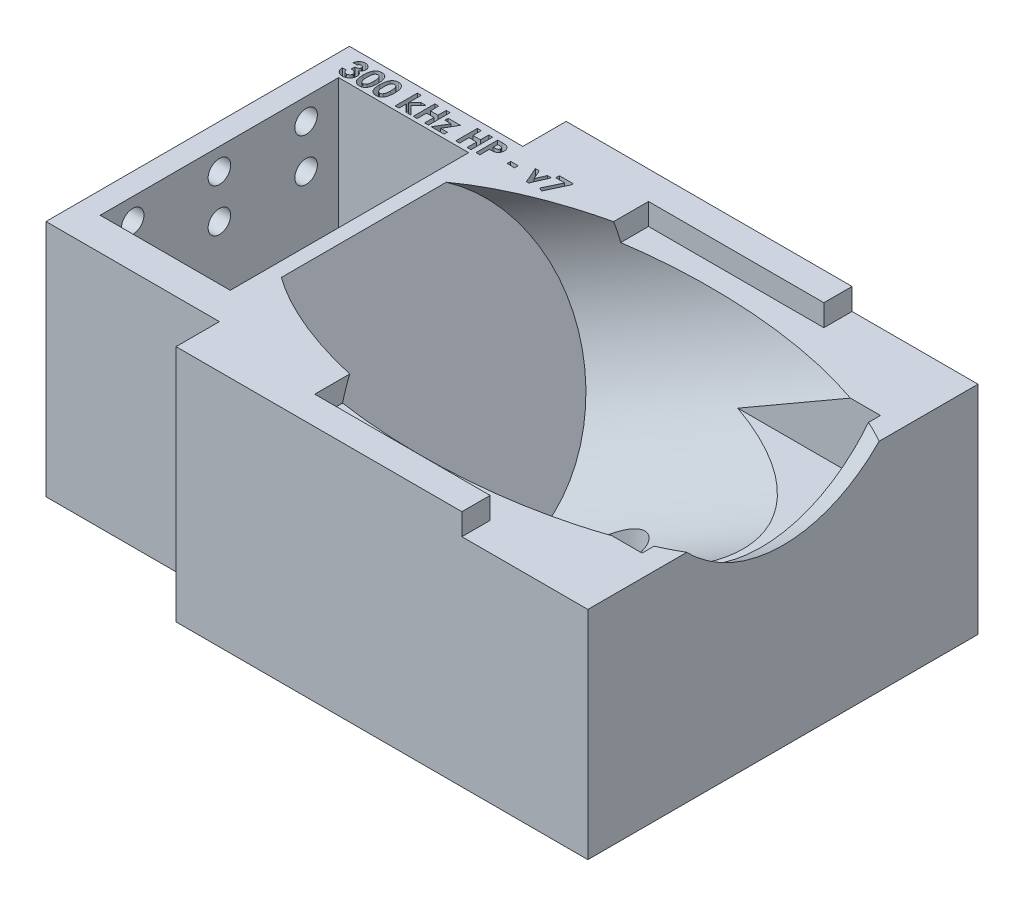
SolidWorks part; units mm, degrees
ref_plane "Front Plane" through (0, 0, 0) normal (0, 0, 1) x (1, 0, 0)
ref_plane "Top Plane" through (0, 0, 0) normal (0, 1, 0) x (1, 0, 0)
ref_plane "Right Plane" through (0, 0, 0) normal (1, 0, 0) x (0, 0, -1)
sketch "Sketch1" plane through (0, 0, 0) normal (0, 0, 1) x (1, 0, 0)
  line L1 (-139.7, -127) -> (88.9, -127)
  line L2 (-139.7, -127) -> (-139.7, 0)
  line L3 (-139.7, 0) -> (88.9, 0)
  line L4 (88.9, -127) -> (88.9, 0)
  line L5 (-139.7, -127) -> (88.9, 0) construction
  line L6 (-139.7, 0) -> (88.9, -127) construction
  point P0 (0, 0)
  dimension "D1" = 228.6
  dimension "D2" = 127
  dimension "D3" = 88.9
extrude "Boss-Extrude1" add sketch "Sketch1" along normal mid plane 101.6
sketch "Sketch10" plane through (0, -127, 0) normal (0, -1, 0) x (1, 0, 0)
  circle A0 centre (0, 0) radius 12.7
  dimension "D1" = 25.4
extrude "Cut-Extrude6" cut sketch "Sketch10" against normal through all
sketch "Sketch2" plane through (0, 0, 0) normal (0, 0, 1) x (1, 0, 0)
  line L0 (-48.125, -30.325) -> (0, -2.54) construction
  line L1 (0, 46.5867) -> (-47.9201, 18.9201)
  line L2 (-50.1425, -26.8306) -> (-69.3975, 6.5201)
  line L3 (-69.3975, 6.5201) -> (-47.9201, 18.9201)
  line L4 (-50.1425, -26.8306) -> (-48.125, -30.325)
  line L5 (-26.6476, -17.925) -> (-47.9201, 18.9201) construction
  line L7 (0, -2.54) -> (87.9882, 48.26)
  line L8 (-83.8, -2.54) -> (0, -2.54) construction
  line L10 (0, -2.54) -> (-48.125, -30.325)
  line L11 (88.9, 0) -> (-139.7, 0) construction
  line L12 (87.9882, 48.26) -> (66.7157, 85.1051)
  line L13 (0, 46.5867) -> (0, -2.54) construction
  line L17 (66.7157, 85.1051) -> (0, 46.5867)
  point P23 (-26.6476, -17.925)
  dimension "D1" = 30
  dimension "D2" = 24.8
  dimension "D3" = 2.54
  dimension "D4" = 30.77
  dimension "D5" = 42.545
  dimension "D6" = 101.6
revolve "Cut-Revolve1" cut sketch "Sketch2" angle 360 about L0
sketch "Sketch11" plane through (0, -127, 0) normal (0, -1, 0) x (1, 0, 0)
  line L1 (13, 13) -> (-13, 13)
  line L2 (13, 13) -> (13, -13)
  line L3 (13, -13) -> (-13, -13)
  line L4 (-13, 13) -> (-13, -13)
  line L5 (13, 13) -> (-13, -13) construction
  line L6 (13, -13) -> (-13, 13) construction
  point P0 (0, 0)
  dimension "D1" = 26
sketch "Sketch22" plane through (0, 0, 0) normal (0, 1, 0) x (1, 0, 0)
  line L0 (88.9, -50.8) -> (-139.7, -50.8) construction
  line L1 (-139.7, 50.8) -> (-114.3, 50.8)
  line L2 (-139.7, 50.8) -> (-139.7, -50.8)
  line L3 (-139.7, -50.8) -> (-114.3, -50.8)
  line L4 (-114.3, 50.8) -> (-114.3, -50.8)
  dimension "D1" = 25.4
extrude "Cut-Extrude17" cut sketch "Sketch22" against normal through all
sketch "Sketch23" plane through (0, -127, 0) normal (0, -1, 0) x (1, 0, 0)
  line L0 (-127, 127) -> (127, -127) construction
  line L1 (-127, 127) -> (127, 127)
  line L2 (-127, 127) -> (-127, -127)
  line L3 (-127, -127) -> (127, -127)
  line L4 (127, 127) -> (127, -127)
  dimension "D1" = 254
  dimension "D2" = 254
extrude "Cut-Extrude18" cut sketch "Sketch23" against normal blind 57.15
sketch "Sketch21" plane through (0, 0, 0) normal (0, 1, 0) x (1, 0, 0)
  line L1 (88.9, -50.8) -> (57.15, -50.8)
  line L2 (88.9, -50.8) -> (88.9, 50.8)
  line L3 (88.9, 50.8) -> (57.15, 50.8)
  line L4 (57.15, -50.8) -> (57.15, 50.8)
  line L5 (88.9, -50.8) -> (-114.3, -50.8) construction
  line L6 (88.9, 50.8) -> (-114.3, 50.8) construction
  line L7 (-114.3, -50.8) -> (-114.3, 50.8) construction
  dimension "D1" = 171.45
extrude "Cut-Extrude16" cut sketch "Sketch21" against normal through all
sketch "Sketch26" plane through (0, 0, 0) normal (0, 1, 0) x (1, 0, 0)
  line L0 (57.15, 50.8) -> (57.15, 33.3829) construction
  line L1 (-12.7, -34.925) -> (50.8, -34.925)
  line L2 (-12.7, -34.925) -> (-12.7, 34.925)
  line L3 (-12.7, 34.925) -> (50.8, 34.925)
  line L4 (50.8, -34.925) -> (50.8, 34.925)
  line L5 (-114.3, -50.8) -> (-114.3, 50.8) construction
  point P4 (-12.7, 0)
  dimension "D1" = 6.35
  dimension "D2" = 101.6
  dimension "D3" = 69.85
extrude "Cut-Extrude21" cut sketch "Sketch26" against normal blind 25.4
sketch "Sketch27" plane through (-114.3, 0, 0) normal (-1, 0, 0) x (0, 0, 1)
  line L0 (50.8, 0) -> (-50.8, 0) construction
  line L1 (-25.4, -6.35) -> (25.4, -6.35) construction
  line L2 (-25.4, -6.35) -> (-25.4, -19.05) construction
  line L3 (-25.4, -19.05) -> (25.4, -19.05) construction
  line L4 (25.4, -6.35) -> (25.4, -19.05) construction
  line L7 (-25.4, -19.05) -> (-25.4, -31.75) construction
  line L8 (-25.4, -31.75) -> (25.4, -31.75) construction
  line L9 (25.4, -19.05) -> (25.4, -31.75) construction
  circle A0 centre (-25.4, -6.35) radius 3.302
  circle A1 centre (0, -6.35) radius 3.302
  circle A2 centre (0, -19.05) radius 3.302
  circle A3 centre (25.4, -6.35) radius 3.302
  circle A4 centre (25.4, -19.05) radius 3.302
  circle A5 centre (-25.4, -19.05) radius 3.302
  circle A7 centre (-25.4, -31.75) radius 3.302 [skipped]
  circle A8 centre (0, -31.75) radius 3.302 [skipped]
  circle A9 centre (25.4, -31.75) radius 3.302 [skipped]
  point P4 (0, -6.35)
  dimension "D5" = 6.604
  dimension "D8" = 25.4
  dimension "D1" = 50.8
  dimension "D2" = 12.7
  dimension "D3" = 6.35
  dimension "D4" = 12.7
  dimension "D6" = 3
  dimension "D7" = 3
extrude "Cut-Extrude22" cut sketch "Sketch27" against normal blind 25.4 and the other way through all
sketch "Sketch28" plane through (0, 0, 0) normal (0, 1, 0) x (1, 0, 0)
  line L0 (-114.3, 36.0198) -> (-43.5568, 36.0198) construction
  line L3 (-114.3, -50.8) -> (-114.3, 50.8) construction
  text T0 "<b>300 kHz HP - v7</b>" font "Century Gothic" height 6.35
extrude "Cut-Extrude23" cut sketch "Sketch28" against normal blind 3.175
sketch "Sketch30" plane through (0, -25.4, 0) normal (0, 1, 0) x (1, 0, 0)
  circle A0 centre (-95.25, 25.4) radius 3.429
  circle A2 centre (-82.55, 25.4) radius 3.429
  circle A3 centre (-82.55, 12.7) radius 3.429
  circle A4 centre (-82.55, 0) radius 3.429
  circle A5 centre (-82.55, -12.7) radius 3.429
  circle A6 centre (-82.55, -25.4) radius 3.429
  circle A7 centre (-95.25, 12.7) radius 3.429
  circle A8 centre (-95.25, 0) radius 3.429
  circle A9 centre (-95.25, -12.7) radius 3.429
  circle A10 centre (-95.25, -25.4) radius 3.429
  dimension "D1" = 6.858
  dimension "D2" = 25.4
  dimension "D3" = 95.25
  dimension "D4" = 2
  dimension "D5" = 5
extrude "Cut-Extrude24" cut sketch "Sketch30" against normal through all
sketch "Sketch31" plane through (0, -25.4, 0) normal (0, 1, 0) x (1, 0, 0)
  line L0 (-107.95, -34.925) -> (-44.1937, -34.925) construction
  line L1 (-107.95, 34.925) -> (-69.85, 34.925)
  line L2 (-107.95, 34.925) -> (-107.95, -34.925)
  line L3 (-107.95, -34.925) -> (-69.85, -34.925)
  line L4 (-69.85, 34.925) -> (-69.85, -34.925)
  dimension "D1" = 38.1
extrude "Cut-Extrude25" cut sketch "Sketch31" against normal offset from surface 6.35 and the other way through all up to face at (-82.55, -69.85, 28.829)
sketch "Sketch32" plane through (0, 0, 0) normal (0, 1, 0) x (1, 0, 0)
  line L0 (57.15, 50.8) -> (57.15, 33.3829) construction
  line L1 (-31.1262, 48.895) -> (57.15, 48.895)
  line L2 (-31.1262, 48.895) -> (-31.1262, -48.895)
  line L3 (-31.1262, -48.895) -> (57.15, -48.895)
  line L4 (57.15, 48.895) -> (57.15, -48.895)
  point P4 (57.15, 0)
  dimension "D1" = 97.79
extrude "Cut-Extrude26" cut sketch "Sketch32" against normal blind 6.35
sketch "Sketch33" plane through (0, 0, 0) normal (0, 1, 0) x (1, 0, 0)
  line L1 (57.15, 50.8) -> (20.2503, 50.8)
  line L2 (57.15, 50.8) -> (57.15, -50.8)
  line L3 (57.15, -50.8) -> (20.2503, -50.8)
  line L4 (20.2503, 50.8) -> (20.2503, -50.8)
  line L5 (57.15, -50.8) -> (-114.3, -50.8) construction
extrude "Cut-Extrude27" cut sketch "Sketch33" against normal blind 6.35
sketch "Sketch34" plane through (0, 0, 50.8) normal (0, 0, 1) x (1, 0, 0)
  line L6 (57.15, -6.35) -> (20.2503, -6.35)
  line L7 (20.2503, -6.35) -> (20.2503, 0)
  line L8 (20.2503, 0) -> (-114.3, 0)
  line L9 (-114.3, 0) -> (-114.3, -69.85)
  line L10 (-114.3, -69.85) -> (57.15, -69.85)
  line L11 (57.15, -69.85) -> (57.15, -6.35)
  line L12 (57.15, -6.35) -> (20.2503, -6.35)
  line L13 (20.2503, -6.35) -> (20.2503, 0)
  line L14 (20.2503, 0) -> (-114.3, 0)
  line L15 (-114.3, 0) -> (-114.3, -69.85)
  line L16 (-114.3, -69.85) -> (57.15, -69.85)
  line L17 (57.15, -69.85) -> (57.15, -6.35)
  dimension "D1" = 0
extrude "Boss-Extrude2" add sketch "Sketch34" along normal blind 6.35
sketch "Sketch35" plane through (0, 0, -50.8) normal (0, 0, -1) x (-1, 0, 0)
  line L6 (-20.2503, 0) -> (-20.2503, -6.35)
  line L7 (-20.2503, -6.35) -> (-57.15, -6.35)
  line L8 (-57.15, -6.35) -> (-57.15, -69.85)
  line L9 (-57.15, -69.85) -> (114.3, -69.85)
  line L10 (114.3, -69.85) -> (114.3, 0)
  line L11 (114.3, 0) -> (-20.2503, 0)
  line L12 (-20.2503, 0) -> (-20.2503, -6.35)
  line L13 (-20.2503, -6.35) -> (-57.15, -6.35)
  line L14 (-57.15, -6.35) -> (-57.15, -69.85)
  line L15 (-57.15, -69.85) -> (114.3, -69.85)
  line L16 (114.3, -69.85) -> (114.3, 0)
  line L17 (114.3, 0) -> (-20.2503, 0)
  dimension "D1" = 0
extrude "Boss-Extrude3" add sketch "Sketch35" along normal blind 6.35
sketch "Sketch36" plane through (0, 0, 0) normal (0, 1, 0) x (1, 0, 0)
  line L0 (-114.3, -57.15) -> (-114.3, 57.15) construction
  line L1 (-114.3, 57.15) -> (-63.5, 57.15)
  line L2 (-114.3, 57.15) -> (-114.3, 44.45)
  line L3 (-114.3, 44.45) -> (-63.5, 44.45)
  line L4 (-63.5, 57.15) -> (-63.5, 44.45)
  line L5 (-114.3, -57.15) -> (-63.5, -57.15)
  line L6 (-114.3, -57.15) -> (-114.3, -44.45)
  line L7 (-114.3, -44.45) -> (-63.5, -44.45)
  line L8 (-63.5, -57.15) -> (-63.5, -44.45)
  dimension "D1" = 50.8
  dimension "D2" = 12.7
extrude "Cut-Extrude28" cut sketch "Sketch36" against normal through all
